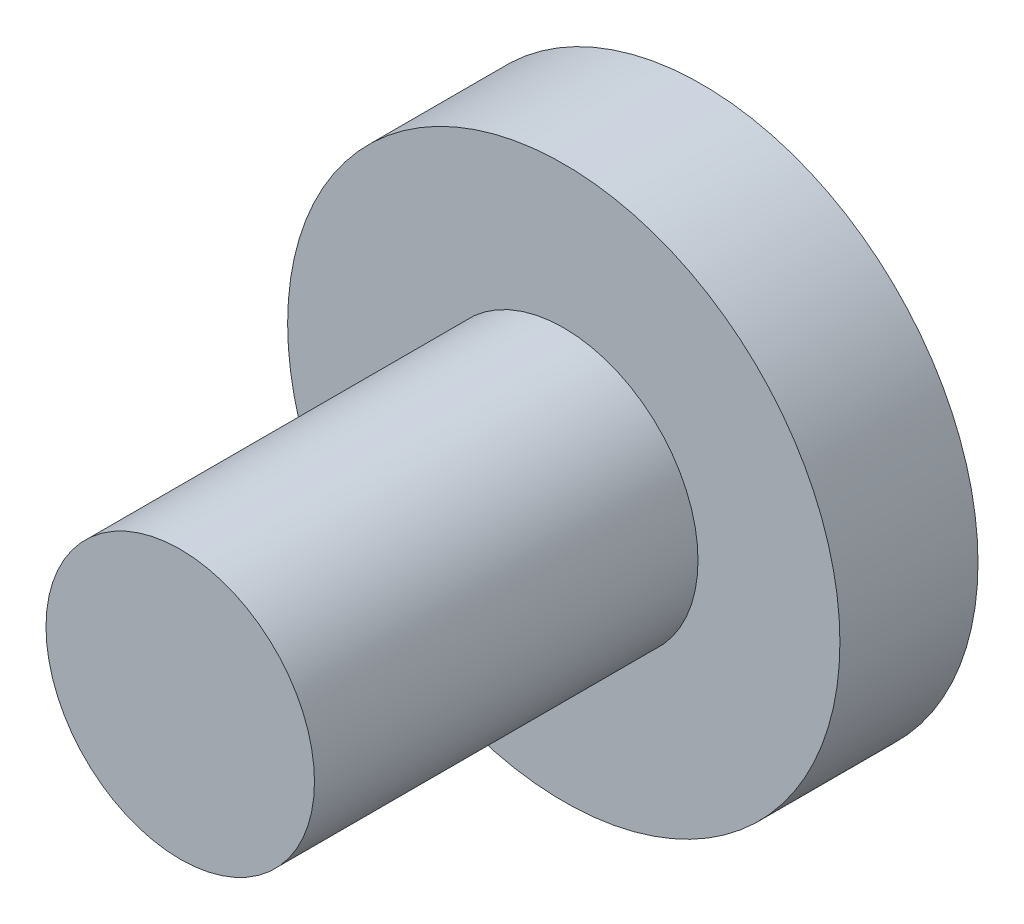
SolidWorks part; units mm, degrees
ref_plane "前视基准面" through (0, 0, 0) normal (0, 0, 1) x (1, 0, 0)
ref_plane "上视基准面" through (0, 0, 0) normal (0, 1, 0) x (1, 0, 0)
ref_plane "右视基准面" through (0, 0, 0) normal (1, 0, 0) x (0, 0, -1)
other "Configuration Table"
sketch "草图1" plane through (0, 0, 0) normal (0, 0, 1) x (1, 0, 0)
  circle A0 centre (0, 0) radius 3.6
  dimension "D1" = 7.2
extrude "凸台-拉伸1" add sketch "草图1" along normal blind 1.8
sketch "草图2" plane through (0, 0, 1.8) normal (0, 0, 1) x (1, 0, 0)
  circle A0 centre (0, 0) radius 1.75
  dimension "D1" = 3.5
extrude "凸台-拉伸2" add sketch "草图2" along normal blind 5
